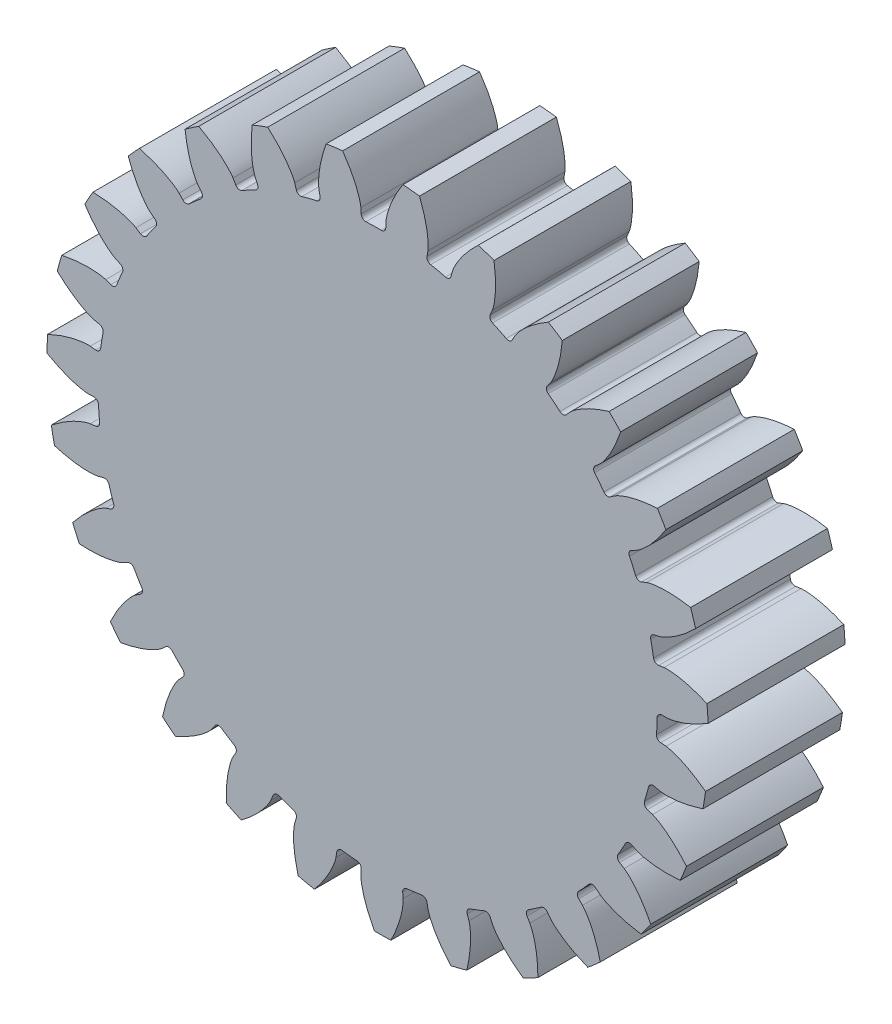
SolidWorks part; units mm, degrees
ref_plane "Front Plane" through (0, 0, 0) normal (0, 0, 1) x (1, 0, 0)
ref_plane "Top Plane" through (0, 0, 0) normal (0, 1, 0) x (1, 0, 0)
ref_plane "Right Plane" through (0, 0, 0) normal (1, 0, 0) x (0, 0, -1)
sketch "Sketch1" plane through (0, 0, 0) normal (0, 0, 1) x (1, 0, 0)
  circle A0 centre (0, 0) radius 7.25
  dimension "D1" = 14.5
extrude "Boss-Extrude1" add sketch "Sketch1" along normal blind 3
sketch "Sketch3" plane through (0, 0, 0) normal (0, 0, 1) x (1, 0, 0)
  line L0 (6.125, 0) -> (6.3429, 0)
  line L2 (6.1021, -0.5294) -> (6.3192, -0.5483)
  line L3 (0, 0) -> (-7.2432, 0.3136) construction
  circle A0 centre (0, 0) radius 6.75 construction
  circle A1 centre (0, 0) radius 6.3429 construction
  arc A2 (6.1021, -0.5294) -> (6.125, 0) centre (0, 0) ccw
  circle A3 centre (0, 0) radius 7.25 construction
  spline S0 degree 4 poles (6.3429, 0) (6.3451, 0) (6.3512, 0.0002) (6.3699, 0.0014) (6.4069, 0.0055) (6.4523, 0.0131) (6.5043, 0.0242) (6.5542, 0.0368) (6.5967, 0.0487) (6.6389, 0.0617) (6.6808, 0.0756) (6.7313, 0.0935) (6.7915, 0.1167) (6.8614, 0.146) (6.9401, 0.1819) (7.0194, 0.2214) (7.0969, 0.2626) (7.1744, 0.3068) (7.2488, 0.3516) (7.3251, 0.4007) (7.3951, 0.4474) (7.4725, 0.5027) (7.5347, 0.5482) (7.6154, 0.6112) (7.6628, 0.6494) (7.7178, 0.6951) (7.7419, 0.716) (7.7568, 0.7288) knots 0 0 0 0 0 0.005377 0.015084 0.04661 0.092111 0.119476 0.146842 0.174209 0.201575 0.228941 0.256307 0.307035 0.361767 0.4165 0.471232 0.525964 0.580697 0.635429 0.690161 0.744894 0.799626 0.854358 0.909091 0.954545 1 1 1 1 1 construction
  spline S1 degree 4 poles (6.3429, 0) (6.3451, 0) (6.3512, 0.0002) (6.3699, 0.0014) (6.4069, 0.0055) (6.4523, 0.0131) (6.5043, 0.0242) (6.5542, 0.0368) (6.5967, 0.0487) (6.6389, 0.0617) (6.6808, 0.0756) (6.7313, 0.0935) (6.7915, 0.1167) (6.8614, 0.146) (6.9401, 0.1819) (7.0194, 0.2214) (7.0969, 0.2626) (7.1744, 0.3068) (7.2488, 0.3516) (7.3251, 0.4007) (7.3951, 0.4474) (7.4725, 0.5027) (7.5347, 0.5482) (7.5979, 0.5976) (7.6286, 0.622) (7.6442, 0.6346) knots 0 0 0 0 0 0.005377 0.015084 0.04661 0.092111 0.119476 0.146842 0.174209 0.201575 0.228941 0.256307 0.307035 0.361767 0.4165 0.471232 0.525964 0.580697 0.635429 0.690161 0.744894 0.799626 0.854358 0.909091 0.909091 0.909091 0.909091 0.909091
  spline S2 degree 4 poles (6.3192, -0.5483) (6.3213, -0.5485) (6.3274, -0.5492) (6.346, -0.552) (6.3824, -0.5593) (6.427, -0.5708) (6.4778, -0.5863) (6.5265, -0.6032) (6.5678, -0.6187) (6.6087, -0.6353) (6.6492, -0.6528) (6.698, -0.675) (6.756, -0.7033) (6.8231, -0.7385) (6.8984, -0.7811) (6.974, -0.8273) (7.0477, -0.875) (7.121, -0.9258) (7.1912, -0.9768) (7.2631, -1.0324) (7.3288, -1.085) (7.4011, -1.1467) (7.4591, -1.1974) (7.5341, -1.2672) (7.578, -1.3093) (7.6288, -1.3596) (7.6511, -1.3825) (7.6648, -1.3966) knots 0 0 0 0 0 0.005377 0.015084 0.04661 0.092111 0.119476 0.146842 0.174209 0.201575 0.228941 0.256307 0.307035 0.361767 0.4165 0.471232 0.525964 0.580697 0.635429 0.690161 0.744894 0.799626 0.854358 0.909091 0.954545 1 1 1 1 1 construction
  spline S3 degree 4 poles (6.3192, -0.5483) (6.3213, -0.5485) (6.3274, -0.5492) (6.346, -0.552) (6.3824, -0.5593) (6.427, -0.5708) (6.4778, -0.5863) (6.5265, -0.6032) (6.5678, -0.6187) (6.6087, -0.6353) (6.6492, -0.6528) (6.698, -0.675) (6.756, -0.7033) (6.8231, -0.7385) (6.8984, -0.7811) (6.974, -0.8273) (7.0477, -0.875) (7.121, -0.9258) (7.1912, -0.9768) (7.2631, -1.0324) (7.3288, -1.085) (7.4011, -1.1467) (7.4591, -1.1974) (7.5178, -1.2521) (7.5463, -1.279) (7.5607, -1.2929) knots 0 0 0 0 0 0.005377 0.015084 0.04661 0.092111 0.119476 0.146842 0.174209 0.201575 0.228941 0.256307 0.307035 0.361767 0.4165 0.471232 0.525964 0.580697 0.635429 0.690161 0.744894 0.799626 0.854358 0.909091 0.909091 0.909091 0.909091 0.909091
  point P5 (6.125, 0)
  point P11 (6.1021, -0.5294)
  dimension "D1" = 13.5
  dimension "D2" = 12.6859
  dimension "D3" = 12.25
  dimension "D4" = 2.479
  dimension "D5" = 2.479
extrude "Cut-Extrude1" cut sketch "Sketch3" against normal through all and the other way through all
fillet "Fillet1" radius 0.1 1 edges at (6.1021, -0.5294, 1.5)
fillet "Fillet2" radius 0.1 1 edges at (6.125, 0, 1.5)
pattern_circular "CirPattern14" count 27 over 360 about axis through (0, 0, 3) along (0, 0, -1) of "Cut-Extrude1", "Fillet1", "Fillet2"
equation "\"P\"= 2'Diametral Pitch"
equation "\"N\"= 27'Number of teeth"
equation "\"phi\"= 20deg'pressure angle"
equation "\"a\"= 1 / \"P\"'addendum"
equation "\"b\"= 1.25 / \"P\"'dedendum"
equation "\"c\"= \"b\" - \"a\"'clearance"
equation "\"dp\"= \"N\" / \"P\"'pitch circle diameter"
equation "\"db\"= \"dp\" * cos ( \"phi\" )'base circle diameter"
equation "\"D1@Sketch1\"= \"dp\" + 2 * \"a\"'Addendum circle diameter"
equation "\"D1@Sketch3\"= \"dp\"'pitch circle"
equation "\"D2@Sketch3\"= \"db\" 'base circle"
equation "\"D3@Sketch3\" = \"dp\" - 2 * \"b\"'dedendum circle"
equation "\"alpha\"= sqr ( \"dp\" ^ 2 - \"db\" ^ 2 ) / \"db\" * 180 / pi - \"phi\"'alpha (deg)"
equation "\"beta\"= ( 360 / ( 4 * \"N\" ) - \"alpha\" ) * 2"
equation "\"D4@Sketch3\"= 360 / ( 4 * \"N\" ) - \"alpha\""
equation "\"D5@Sketch3\"= 360 / ( 4 * \"N\" ) - \"alpha\""
